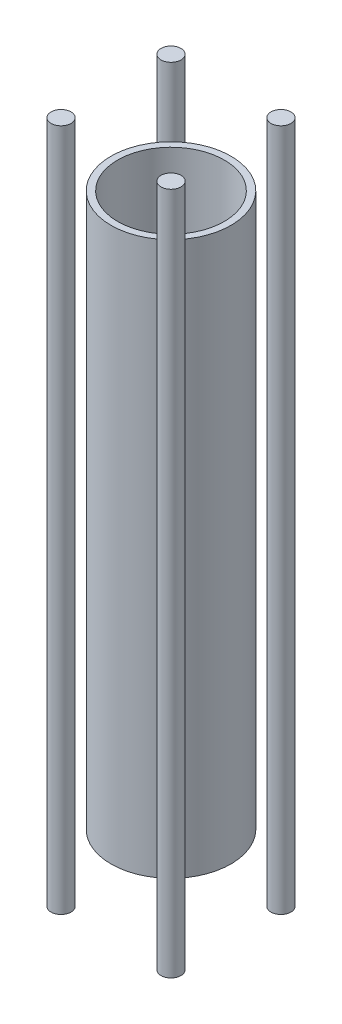
SolidWorks part; units mm, degrees
material "6061-T6 (SS)"
ref_plane "Front Plane" through (0, 0, 0) normal (0, 0, 1) x (1, 0, 0)
ref_plane "Top Plane" through (0, 0, 0) normal (0, 1, 0) x (1, 0, 0)
ref_plane "Right Plane" through (0, 0, 0) normal (1, 0, 0) x (0, 0, -1)
sketch "Sketch1" plane through (0, 0, 0) normal (0, 1, 0) x (1, 0, 0)
  circle A0 centre (0, 0) radius 16
  circle A1 centre (0, 0) radius 18
  dimension "D1" = 32
  dimension "D2" = 36
extrude "Boss-Extrude1" add sketch "Sketch1" along normal blind 166
sketch "Sketch2" plane through (0, 0, 0) normal (0, 1, 0) x (1, 0, 0)
  line L0 (-16.5, 16.5) -> (0, 0) construction
  line L1 (0, 0) -> (0, 5.856) construction
  circle A0 centre (-16.5, 16.5) radius 3
  circle A1 centre (16.5, 16.5) radius 3
  circle A2 centre (16.5, -16.5) radius 3
  circle A3 centre (-16.5, -16.5) radius 3
  point P14 (0, 0)
  dimension "D1" = 6
  dimension "D2" = 45
  dimension "D4" = 33
  dimension "D3" = 4
extrude "Boss-Extrude2" add sketch "Sketch2" along normal blind 185 and the other way blind 20 separate body
